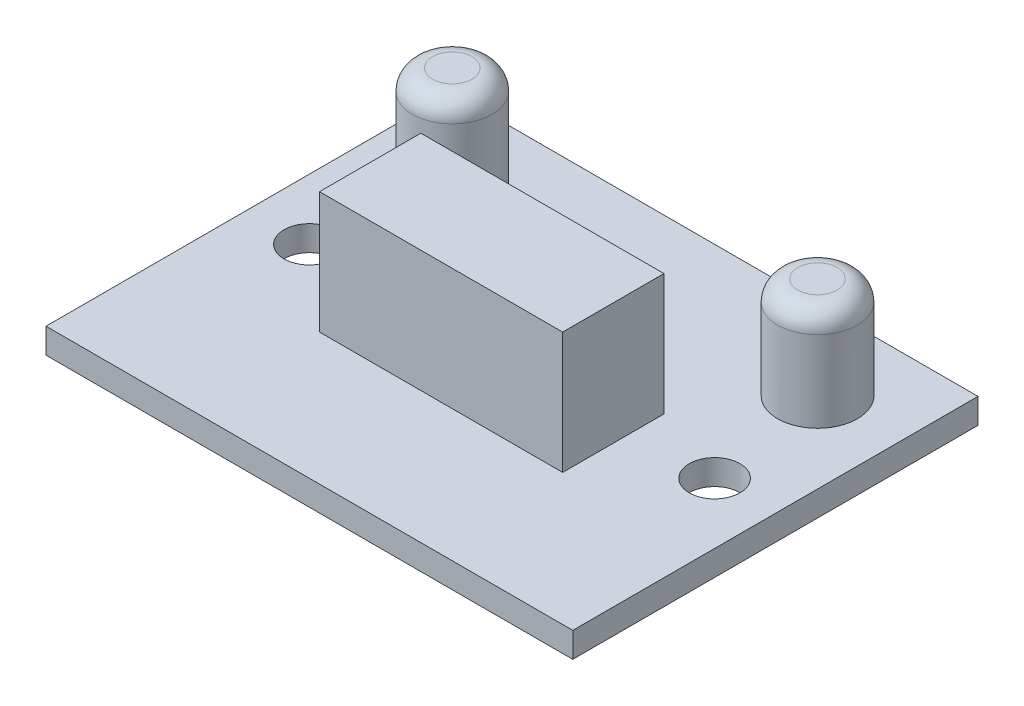
SolidWorks part; units mm, degrees
material "A-Glass Fiber"
ref_plane "Front" through (0, 0, 0) normal (0, 0, 1) x (1, 0, 0)
ref_plane "Top" through (0, 0, 0) normal (0, 1, 0) x (1, 0, 0)
ref_plane "Right" through (0, 0, 0) normal (1, 0, 0) x (0, 0, -1)
sketch "Sketch1" plane through (0, 0, 0) normal (0, 1, 0) x (1, 0, 0)
  line L0 (0, 12.7) -> (33.02, 12.7) construction
  line L1 (0, 0) -> (33.02, 0)
  line L2 (0, 0) -> (0, 25.4)
  line L3 (0, 25.4) -> (33.02, 25.4)
  line L4 (33.02, 0) -> (33.02, 25.4)
  circle A0 centre (3.81, 12.7) radius 1.5875
  circle A1 centre (29.21, 12.7) radius 1.5875
  dimension "D5" = 3.175
  dimension "D1" = 33.02
  dimension "D2" = 25.4
  dimension "D3" = 25.4
  dimension "D4" = 3.81
extrude "Boss-Extrude1" add sketch "Sketch1" along normal blind 1.5748
sketch "Sketch2" plane through (0, 1.5748, 0) normal (0, 1, 0) x (1, 0, 0)
  line L0 (16.51, 0) -> (16.51, 25.4) construction
  line L1 (8.89, 14.605) -> (24.13, 14.605)
  line L2 (8.89, 14.605) -> (8.89, 8.255)
  line L3 (8.89, 8.255) -> (24.13, 8.255)
  line L4 (24.13, 14.605) -> (24.13, 8.255)
  line L5 (0, 0) -> (33.02, 0) construction
  line L6 (33.02, 25.4) -> (0, 25.4) construction
  line L7 (8.89, 11.43) -> (24.13, 11.43) construction
  dimension "D1" = 15.24
  dimension "D2" = 6.35
  dimension "D3" = 11.43
extrude "Boss-Extrude2" add sketch "Sketch2" along normal blind 7.62
sketch "Sketch3" plane through (0, 1.5748, 0) normal (0, 1, 0) x (1, 0, 0)
  line L0 (16.51, 25.4) -> (16.51, 16.2512) construction
  line L1 (33.02, 25.4) -> (0, 25.4) construction
  circle A0 centre (5.0633, 20.4048) radius 2.5
  circle A1 centre (27.9567, 20.4048) radius 2.5
  dimension "D1" = 5
extrude "Boss-Extrude3" add sketch "Sketch3" along normal blind 6.35
fillet "Fillet1" radius 1.27 2 edges at (27.9567, 7.9248, -17.9048) (5.0633, 7.9248, -17.9048)
